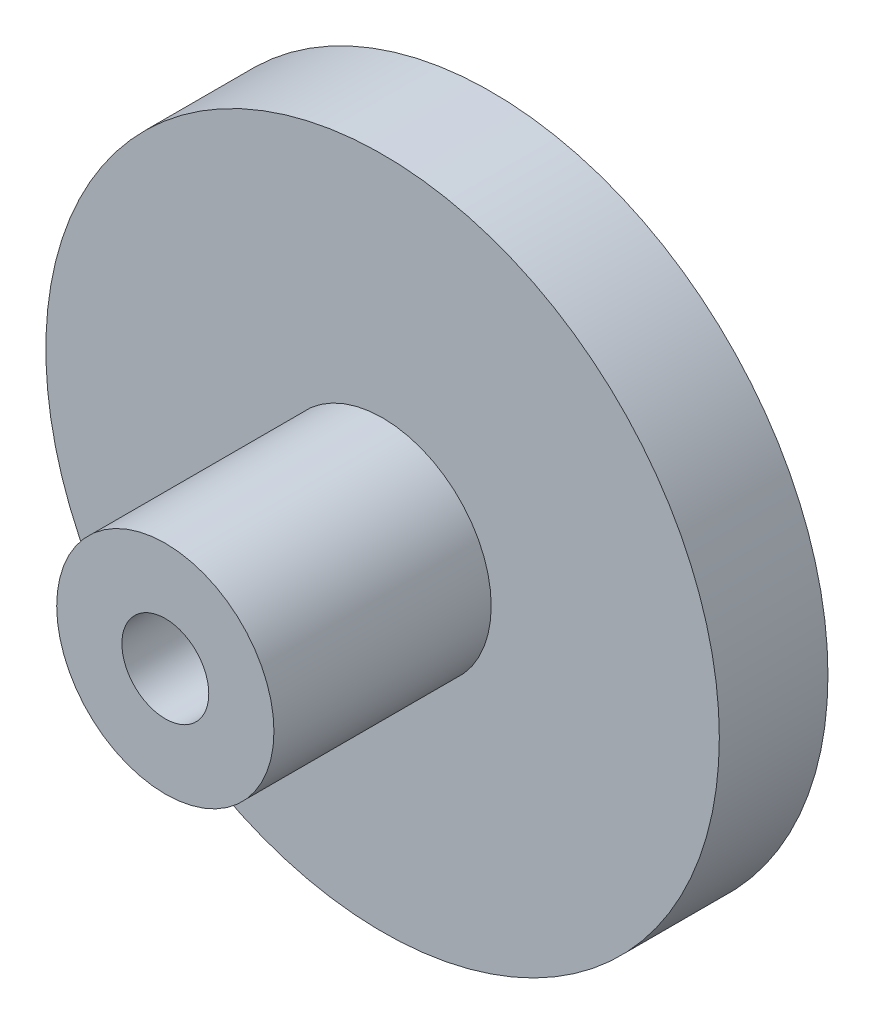
SolidWorks part; units mm, degrees
ref_plane "Front Plane" through (0, 0, 0) normal (0, 0, 1) x (1, 0, 0)
ref_plane "Top Plane" through (0, 0, 0) normal (0, 1, 0) x (1, 0, 0)
ref_plane "Right Plane" through (0, 0, 0) normal (1, 0, 0) x (0, 0, -1)
sketch "Sketch1" plane through (0, 0, 0) normal (0, 0, 1) x (1, 0, 0)
  circle A0 centre (0, 0) radius 15.5
  dimension "D1" = 31
extrude "Boss-Extrude1" add sketch "Sketch1" along normal blind 5
sketch "Sketch2" plane through (0, 0, 5) normal (0, 0, 1) x (1, 0, 0)
  circle A0 centre (0, 0) radius 5
  dimension "20" = 10
extrude "Boss-Extrude3" add sketch "Sketch2" along normal blind 10 contours A0
sketch "Sketch3" plane through (0, 0, 15) normal (0, 0, 1) x (1, 0, 0)
  circle A0 centre (0, 0) radius 2
  dimension "D1" = 4
extrude "Cut-Extrude1" cut sketch "Sketch3" against normal blind 3
